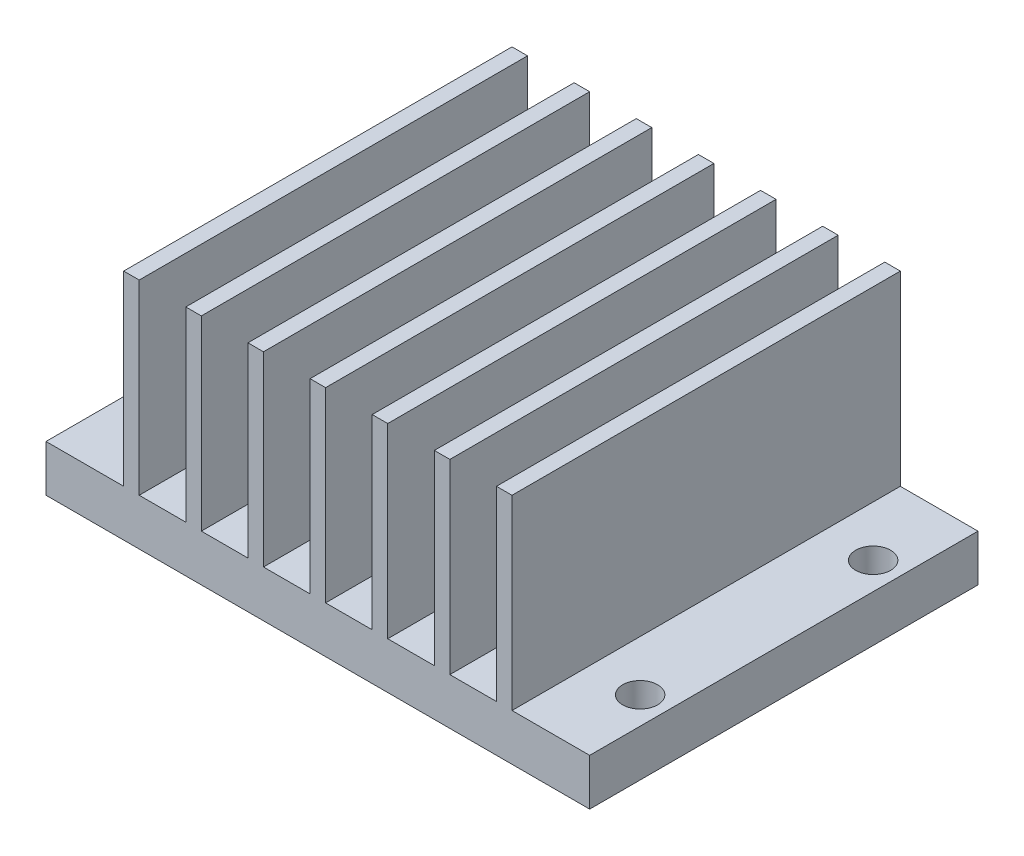
SolidWorks part; units mm, degrees
ref_plane "前视基准面" through (0, 0, 0) normal (0, 0, 1) x (1, 0, 0)
ref_plane "上视基准面" through (0, 0, 0) normal (0, 1, 0) x (1, 0, 0)
ref_plane "右视基准面" through (0, 0, 0) normal (1, 0, 0) x (0, 0, -1)
sketch "草图1" plane through (0, 0, 0) normal (0, 1, 0) x (1, 0, 0)
  line L0 (-35, 25) -> (35, 25)
  line L1 (35, 25) -> (35, -25)
  line L2 (35, -25) -> (-35, -25)
  line L3 (-35, -25) -> (-35, 25)
extrude "凸台-拉伸1" add sketch "草图1" along normal blind 6
ref_plane "基准面1" through (0, 5.5, 0) normal (0, 1, 0) x (1, 0, 0)
sketch "草图2" plane through (0, 5.5, 0) normal (0, 1, 0) x (1, 0, 0)
  line L0 (-25, 25) -> (-23, 25)
  line L1 (-23, 25) -> (-23, -25)
  line L2 (-23, -25) -> (-25, -25)
  line L3 (-25, -25) -> (-25, 25)
  line L4 (-17, 25) -> (-15, 25)
  line L5 (-15, 25) -> (-15, -25)
  line L6 (-15, -25) -> (-17, -25)
  line L7 (-17, -25) -> (-17, 25)
  line L8 (-9, 25) -> (-7, 25)
  line L9 (-7, 25) -> (-7, -25)
  line L10 (-7, -25) -> (-9, -25)
  line L11 (-9, -25) -> (-9, 25)
  line L12 (-1, 25) -> (1, 25)
  line L13 (1, 25) -> (1, -25)
  line L14 (1, -25) -> (-1, -25)
  line L15 (-1, -25) -> (-1, 25)
  line L16 (7, 25) -> (9, 25)
  line L17 (9, 25) -> (9, -25)
  line L18 (9, -25) -> (7, -25)
  line L19 (7, -25) -> (7, 25)
  line L20 (15, 25) -> (17, 25)
  line L21 (17, 25) -> (17, -25)
  line L22 (17, -25) -> (15, -25)
  line L23 (15, -25) -> (15, 25)
  line L24 (23, 25) -> (25, 25)
  line L25 (25, 25) -> (25, -25)
  line L26 (25, -25) -> (23, -25)
  line L27 (23, -25) -> (23, 25)
extrude "凸台-拉伸2" add sketch "草图2" along normal blind 24.5
ref_plane "基准面2" through (0, 30, 0) normal (0, 1, 0) x (1, 0, 0)
sketch "草图3" plane through (0, 30, 0) normal (0, 1, 0) x (1, 0, 0)
  circle A0 centre (-31.5, 15) radius 2.25
  circle A1 centre (-31.5, -15) radius 2.25
  circle A2 centre (31.5, 15) radius 2.25
  circle A3 centre (31.5, -15) radius 2.25
extrude "切除-拉伸1" cut sketch "草图3" against normal through all
